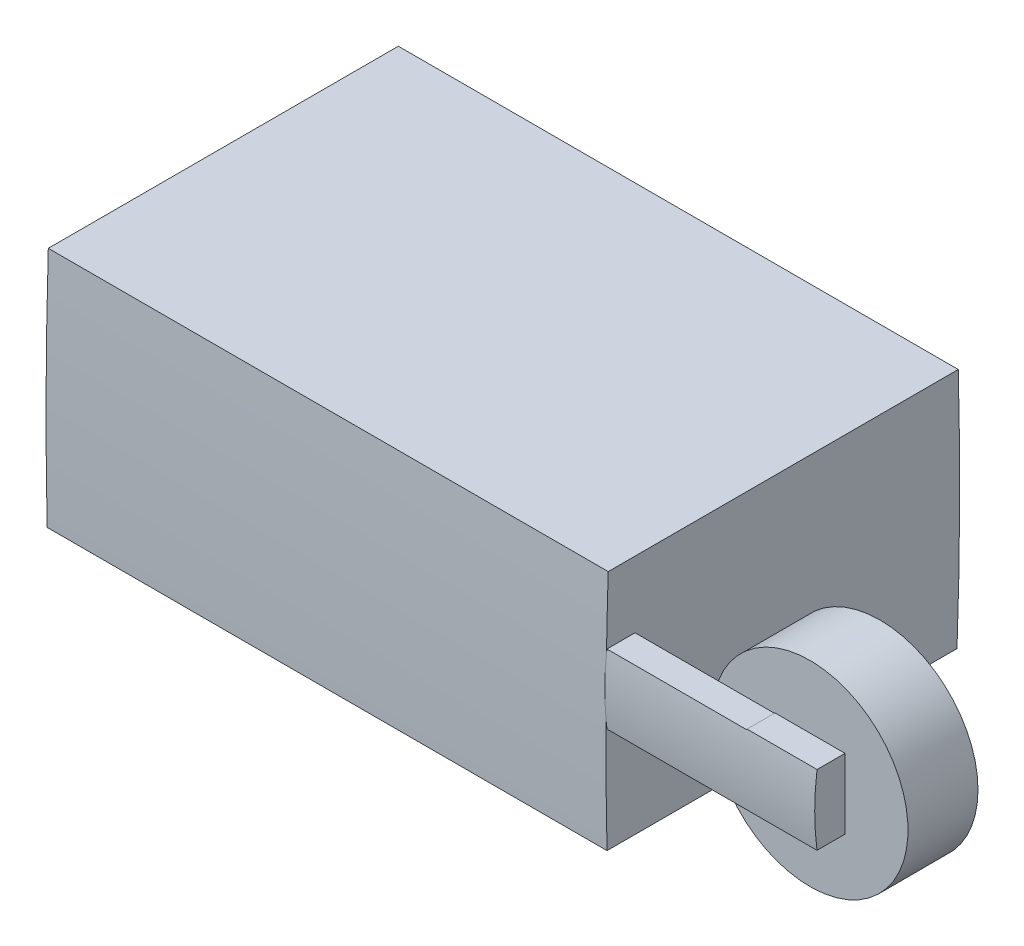
SolidWorks part; units mm, degrees
ref_plane "Front Plane" through (0, 0, 0) normal (0, 0, 1) x (1, 0, 0)
ref_plane "Top Plane" through (0, 0, 0) normal (0, 1, 0) x (1, 0, 0)
ref_plane "Right Plane" through (0, 0, 0) normal (1, 0, 0) x (0, 0, -1)
sketch "Sketch1" plane through (0, 0, 0) normal (0, 0, 1) x (1, 0, 0)
  circle A0 centre (0, 0) radius 14
  circle A1 centre (0, 0) radius 10
  circle A2 centre (0, 0) radius 5.5
extrude "Boss-Extrude1" add sketch "Sketch1" along normal blind 10 contours A0
sketch "Sketch2" plane through (0, 0, 0) normal (0, 0, -1) x (-1, 0, 0)
  circle A0 centre (0, 0) radius 2.25
extrude "Cut-Extrude1" cut sketch "Sketch2" against normal blind 5
sketch "Sketch3" plane through (0, 0, 0) normal (0, 0, -1) x (-1, 0, 0)
  circle A0 centre (0, 0) radius 5
extrude "Cut-Extrude2" cut sketch "Sketch3" against normal blind 1.8
sketch "Sketch4" plane through (0, 0, 10) normal (0, 0, 1) x (1, 0, 0)
  line L1 (-5, 5) -> (5, 5)
  line L2 (-5, 5) -> (-5, -5)
  line L3 (-5, -5) -> (5, -5)
  line L4 (5, 5) -> (5, -5)
  line L5 (-5, 5) -> (5, -5) construction
  line L6 (-5, -5) -> (5, 5) construction
  point P0 (0, 0)
  dimension "D1" = 10
  dimension "D2" = 10
extrude "Boss-Extrude2" add sketch "Sketch4" along normal blind 8
sketch "Sketch6" plane through (-5, 0, 0) normal (-1, 0, 0) x (0, 0, 1)
  line L0 (10, 5) -> (10, -5) construction
  line L1 (10, 4.9129) -> (18, 4.9129)
  line L2 (10, 4.9129) -> (10, -5)
  line L3 (10, -5) -> (18, -5)
  line L4 (18, 4.9129) -> (18, -5)
extrude "Boss-Extrude3" add sketch "Sketch6" along normal blind 20
sketch "Sketch7" plane through (5, 0, 0) normal (1, 0, 0) x (0, 0, -1)
  line L0 (-18, 5) -> (-18, -5)
  line L1 (-18, -5) -> (-14, -5)
  line L2 (-18, -5) -> (-10, -5) construction
  line L3 (-18, 5) -> (-14, 5)
  line L4 (-18, 5) -> (-10, 5) construction
  arc A2 (-14, -5) -> (-14, 5) centre (23.6696, 0) cw
extrude "Cut-Extrude3" cut sketch "Sketch7" against normal blind 30
sketch "Sketch8" plane through (-25, 0, 0) normal (-1, 0, 0) x (0, 0, 1)
  line L4 (-36.1803, 14.4036) -> (13.8311, 14.4036)
  line L5 (-36, -20.0436) -> (14, -20.0436)
  arc A0 (13.8311, 14.4036) -> (14, -20.0436) centre (-602.0691, -5.8394) cw
  arc A1 (-36, -20.0436) -> (-36.1803, 14.4036) centre (494.3169, -0.0436) cw
extrude "Boss-Extrude4" add sketch "Sketch8" along normal blind 80
